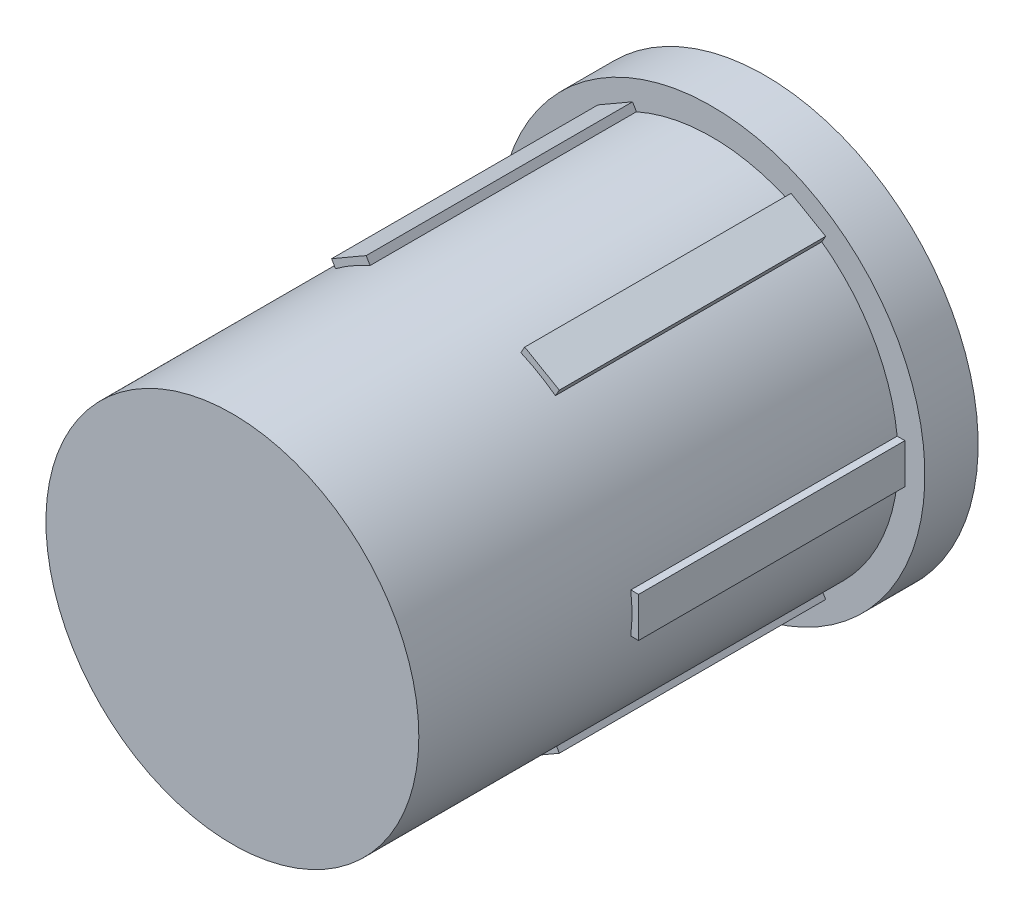
SolidWorks part; units mm, degrees
ref_plane "前视基准面" through (0, 0, 0) normal (0, 0, 1) x (1, 0, 0)
ref_plane "上视基准面" through (0, 0, 0) normal (0, 1, 0) x (1, 0, 0)
ref_plane "右视基准面" through (0, 0, 0) normal (1, 0, 0) x (0, 0, -1)
sketch "草图1" plane through (0, 0, 0) normal (0, 0, 1) x (1, 0, 0)
  circle A0 centre (0, 0) radius 1.4
  dimension "D1" = 2.8
extrude "凸台-拉伸1" add sketch "草图1" along normal blind 3.6
sketch "草图2" plane through (0, 0, 0) normal (0, 0, -1) x (-1, 0, 0)
  circle A0 centre (0, 0) radius 1.6
  dimension "D1" = 3.2
extrude "凸台-拉伸2" add sketch "草图2" along normal blind 0.4
sketch "草图3" plane through (0, 0, 0) normal (0, 1, 0) x (1, 0, 0)
  line L0 (-1.4, 0) -> (1.4, 0) construction
  line L1 (-1.45, 0) -> (-1.3299, 0)
  line L2 (-1.45, 0) -> (-1.45, -2)
  line L3 (-1.45, -2) -> (-1.3299, -2)
  line L4 (-1.3299, 0) -> (-1.3299, -2)
  dimension "D1" = 2
  dimension "D2" = 1.45
extrude "凸台-拉伸3" add sketch "草图3" along normal mid plane 0.3
pattern_circular "阵列(圆周)1" count 6 over 360 about axis through (0, 0, 0) along (0, 0, 1) of "凸台-拉伸3"
